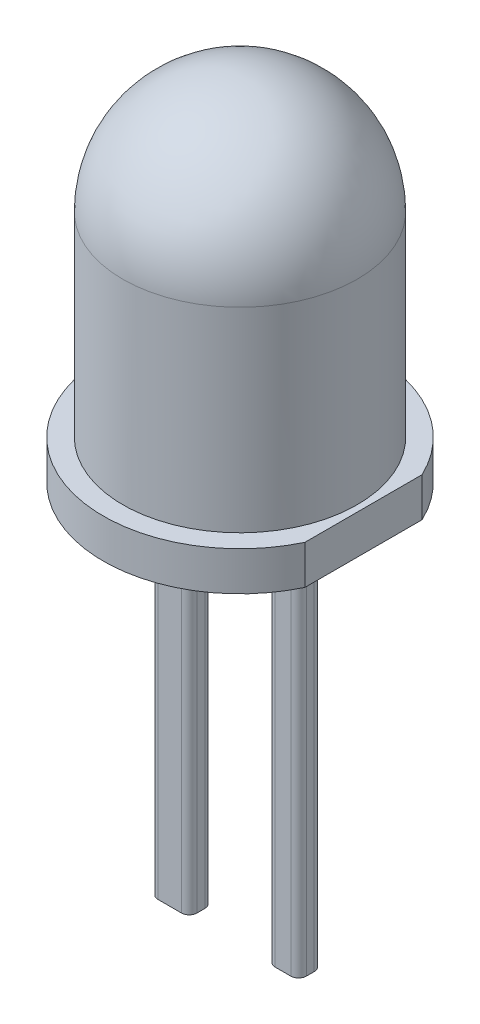
SolidWorks part; units mm, degrees
ref_plane "Ebene vorne" through (0, 0, 0) normal (0, 0, 1) x (1, 0, 0)
ref_plane "Ebene oben" through (0, 0, 0) normal (0, 1, 0) x (1, 0, 0)
ref_plane "Ebene rechts" through (0, 0, 0) normal (1, 0, 0) x (0, 0, -1)
sketch "Skizze2" plane through (0, 0, 0) normal (0, 0, 1) x (1, 0, 0)
  line L0 (0, 0) -> (0, 73.4838) construction
  line L1 (0, 0) -> (-1.75, 0)
  line L2 (-1.75, 0) -> (-1.75, 0.5)
  line L3 (-1.75, 0.5) -> (-1.5, 0.5)
  line L4 (-1.5, 0.5) -> (-1.5, 3)
  line L5 (0, 4.5) -> (0, 0)
  arc A0 (-1.5, 3) -> (0, 4.5) centre (0, 3) cw
  dimension "D1" = 4.5
  dimension "D2" = 0.5
  dimension "D3" = 1.75
  dimension "D4" = 2.5
  dimension "D5" = 1.5
revolve "Rotation1" add sketch "Skizze2" angle 360 about L0
sketch "Skizze3" plane through (0, 0, 0) normal (0, -1, 0) x (1, 0, 0)
  line L0 (1.5811, -0.75) -> (1.5811, 0.75)
  line L1 (0, 0) -> (1.75, 0) construction
  circle A0 centre (0, 0) radius 1.75 construction
  arc A1 (1.5811, -0.75) -> (1.5811, 0.75) centre (0, 0) ccw
  dimension "D1" = 1.5
extrude "Schnitt-Linear austragen1" cut sketch "Skizze3" against normal blind 1
sketch "Skizze4" plane through (0, 0, 0) normal (0, -1, 0) x (1, 0, 0)
  line L0 (-1.75, 0) -> (1.5811, 0) construction
  line L1 (0, 0) -> (0, 1.75) construction
  line L3 (1.5811, 0.75) -> (1.5811, -0.75) construction
  line L4 (0.6, 0.15) -> (0.8, 0.15)
  line L5 (0.5, 0.05) -> (0.5, -0.05)
  line L6 (0.6, -0.15) -> (0.8, -0.15)
  line L7 (0.9, 0.05) -> (0.9, -0.05)
  line L8 (-0.9, 0.15) -> (-0.6, 0.15)
  line L9 (-1, 0.05) -> (-1, -0.05)
  line L10 (-0.9, -0.15) -> (-0.6, -0.15)
  line L11 (-0.5, 0.05) -> (-0.5, -0.05)
  arc A0 (1.5811, 0.75) -> (1.5811, -0.75) centre (0, 0) ccw construction
  arc A1 (1.5811, 0.75) -> (1.5811, -0.75) centre (0, 0) ccw construction
  arc A2 (0.8, 0.15) -> (0.9, 0.05) centre (0.8, 0.05) cw
  arc A3 (0.6, 0.15) -> (0.5, 0.05) centre (0.6, 0.05) ccw
  arc A4 (0.5, -0.05) -> (0.6, -0.15) centre (0.6, -0.05) ccw
  arc A5 (0.8, -0.15) -> (0.9, -0.05) centre (0.8, -0.05) ccw
  arc A6 (-0.6, -0.15) -> (-0.5, -0.05) centre (-0.6, -0.05) ccw
  arc A7 (-0.6, 0.15) -> (-0.5, 0.05) centre (-0.6, 0.05) cw
  arc A8 (-0.9, 0.15) -> (-1, 0.05) centre (-0.9, 0.05) ccw
  arc A9 (-1, -0.05) -> (-0.9, -0.15) centre (-0.9, -0.05) ccw
  point P24 (0.9, 0.15)
  point P29 (0.5, -0.15)
  point P32 (0.9, -0.15)
  point P35 (-0.5, -0.15)
  point P40 (-1, 0.15)
  point P43 (-1, -0.15)
  dimension "D7" = 0.1
  dimension "D1" = 0.3
  dimension "D2" = 0.4
  dimension "D3" = 0.3
  dimension "D4" = 0.5
  dimension "D5" = 0.5
  dimension "D6" = 0.5
extrude "Linear austragen1" add sketch "Skizze4" along normal blind 5
